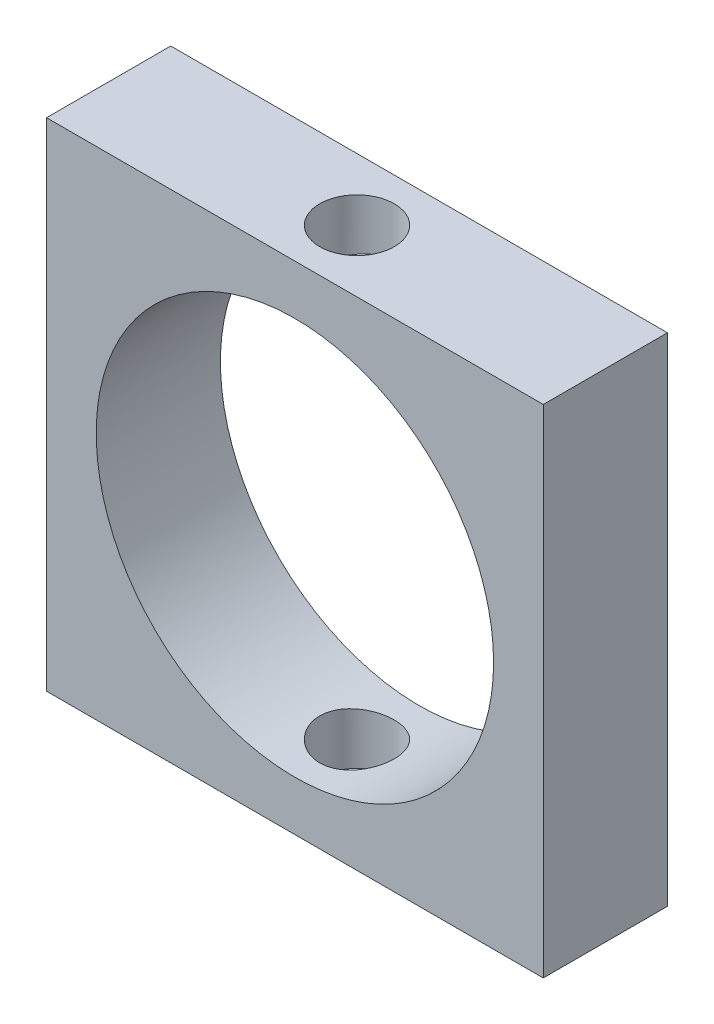
SolidWorks part; units mm, degrees
ref_plane "Front Plane" through (0, 0, 0) normal (0, 0, 1) x (1, 0, 0)
ref_plane "Top Plane" through (0, 0, 0) normal (0, 1, 0) x (1, 0, 0)
ref_plane "Right Plane" through (0, 0, 0) normal (1, 0, 0) x (0, 0, -1)
sketch "Sketch1" plane through (0, 0, 0) normal (0, 0, 1) x (1, 0, 0)
  line L1 (-10, -10) -> (10, -10)
  line L2 (-10, -10) -> (-10, 10)
  line L3 (-10, 10) -> (10, 10)
  line L4 (10, -10) -> (10, 10)
  line L5 (-10, -10) -> (10, 10) construction
  line L6 (-10, 10) -> (10, -10) construction
  circle A0 centre (0, 0) radius 8
extrude "Boss-Extrude1" add sketch "Sketch1" along normal blind 5
sketch "Sketch3" plane through (0, 10, 0) normal (0, 1, 0) x (1, 0, 0)
  circle A0 centre (0, -2.5) radius 1.5
extrude "Cut-Extrude1" cut sketch "Sketch3" against normal blind 20
